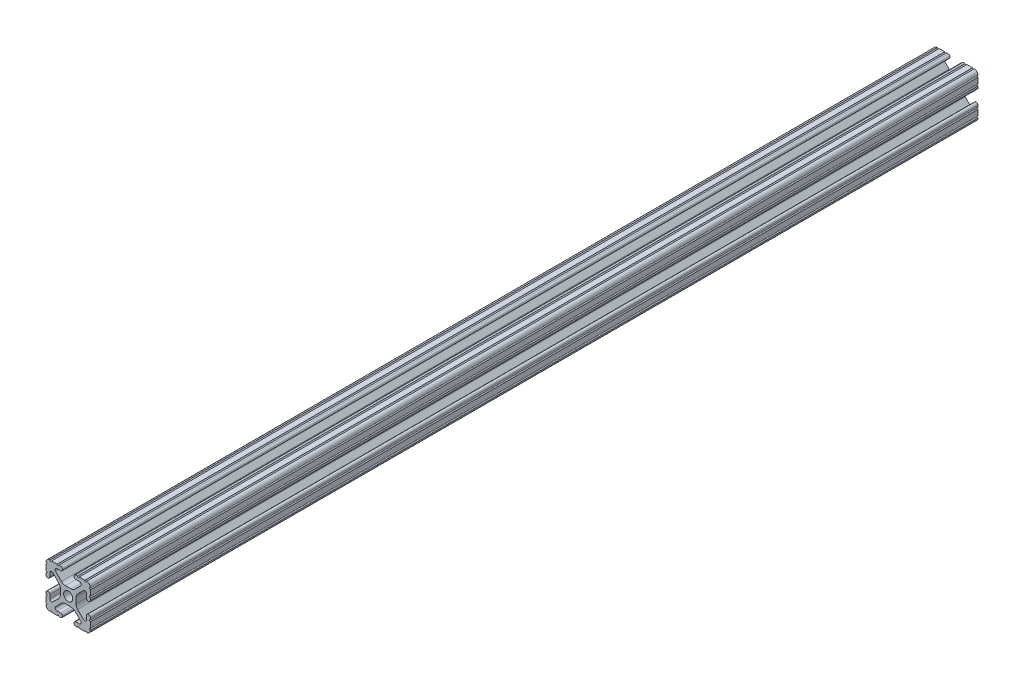
SolidWorks part; units mm, degrees
ref_plane "Front Plane" through (0, 0, 0) normal (0, 0, 1) x (1, 0, 0)
ref_plane "Top Plane" through (0, 0, 0) normal (0, 1, 0) x (1, 0, 0)
ref_plane "Right Plane" through (0, 0, 0) normal (1, 0, 0) x (0, 0, -1)
ref_plane "Plane1" through (0, 0, -25.4) normal (0, 0, -1) x (-1, 0, 0)
sketch "Sketch1" plane through (0, 0, -25.4) normal (0, 0, -1) x (-1, 0, 0)
  line L0 (12.7, -9.5504) -> (12.7, -6.3331)
  line L1 (12.7, -5.3171) -> (12.7, -4.3434)
  line L2 (10.4902, -4.3434) -> (10.4902, -6.4748)
  line L3 (8.7558, -7.1932) -> (5.4257, -3.8632)
  line L4 (4.4958, -1.6181) -> (4.4958, 1.6181)
  line L5 (5.4257, 3.8632) -> (8.7558, 7.1932)
  line L6 (10.4902, 6.4748) -> (10.4902, 4.3434)
  line L7 (12.7, 4.3434) -> (12.7, 5.3171)
  line L8 (12.7, 6.3331) -> (12.7, 9.5504)
  line L9 (9.5504, 12.7) -> (6.3331, 12.7)
  line L10 (5.3171, 12.7) -> (4.3434, 12.7)
  line L11 (4.3434, 10.4902) -> (6.4748, 10.4902)
  line L12 (7.1932, 8.7558) -> (3.8632, 5.4257)
  line L13 (1.6181, 4.4958) -> (-1.6181, 4.4958)
  line L14 (-3.8632, 5.4257) -> (-7.1932, 8.7558)
  line L15 (-6.4748, 10.4902) -> (-4.3434, 10.4902)
  line L16 (-4.3434, 12.7) -> (-5.3171, 12.7)
  line L17 (-6.3331, 12.7) -> (-9.5504, 12.7)
  line L18 (-12.7, 9.5504) -> (-12.7, 6.3331)
  line L19 (-12.7, 5.3171) -> (-12.7, 4.3434)
  line L20 (-10.4902, 4.3434) -> (-10.4902, 6.4748)
  line L21 (-8.7558, 7.1932) -> (-5.4257, 3.8632)
  line L22 (-4.4958, 1.6181) -> (-4.4958, -1.6181)
  line L23 (-5.4257, -3.8632) -> (-8.7558, -7.1932)
  line L24 (-10.4902, -6.4748) -> (-10.4902, -4.3434)
  line L25 (-12.7, -4.3434) -> (-12.7, -5.3171)
  line L26 (-12.7, -6.3331) -> (-12.7, -9.5504)
  line L27 (-9.5504, -12.7) -> (-6.3331, -12.7)
  line L28 (-5.3171, -12.7) -> (-4.3434, -12.7)
  line L29 (-4.3434, -10.4902) -> (-6.4748, -10.4902)
  line L30 (-7.1932, -8.7558) -> (-3.8632, -5.4257)
  line L31 (-1.6181, -4.4958) -> (1.6181, -4.4958)
  line L32 (3.8632, -5.4257) -> (7.1932, -8.7558)
  line L33 (6.4748, -10.4902) -> (4.3434, -10.4902)
  line L34 (4.3434, -12.7) -> (5.3171, -12.7)
  line L35 (6.3331, -12.7) -> (9.5504, -12.7)
  arc A0 (12.6998, -10.5664) -> (12.7, -9.5504) centre (12.7, -10.0584) cw
  arc A1 (12.7, -6.3331) -> (12.7, -5.3171) centre (12.7, -5.8251) cw
  arc A2 (12.7, -4.3434) -> (10.4902, -4.3434) centre (11.5951, -4.3434) ccw
  arc A3 (10.4902, -6.4748) -> (8.7558, -7.1932) centre (9.4742, -6.4748) cw
  arc A4 (5.4257, -3.8632) -> (4.4958, -1.6181) centre (7.6708, -1.6181) cw
  arc A5 (4.4958, 1.6181) -> (5.4257, 3.8632) centre (7.6708, 1.6181) cw
  arc A6 (8.7558, 7.1932) -> (10.4902, 6.4748) centre (9.4742, 6.4748) cw
  arc A7 (10.4902, 4.3434) -> (12.7, 4.3434) centre (11.5951, 4.3434) ccw
  arc A8 (12.7, 5.3171) -> (12.7, 6.3331) centre (12.7, 5.8251) cw
  arc A9 (12.7, 9.5504) -> (12.6998, 10.5664) centre (12.7, 10.0584) cw
  arc A10 (12.6998, 10.5664) -> (10.5664, 12.6998) centre (10.5918, 10.5918) ccw
  arc A11 (10.5664, 12.6998) -> (9.5504, 12.7) centre (10.0584, 12.7) cw
  arc A12 (6.3331, 12.7) -> (5.3171, 12.7) centre (5.8251, 12.7) cw
  arc A13 (4.3434, 12.7) -> (4.3434, 10.4902) centre (4.3434, 11.5951) ccw
  arc A14 (6.4748, 10.4902) -> (7.1932, 8.7558) centre (6.4748, 9.4742) cw
  arc A15 (3.8632, 5.4257) -> (1.6181, 4.4958) centre (1.6181, 7.6708) cw
  arc A16 (-1.6181, 4.4958) -> (-3.8632, 5.4257) centre (-1.6181, 7.6708) cw
  arc A17 (-7.1932, 8.7558) -> (-6.4748, 10.4902) centre (-6.4748, 9.4742) cw
  arc A18 (-4.3434, 10.4902) -> (-4.3434, 12.7) centre (-4.3434, 11.5951) ccw
  arc A19 (-5.3171, 12.7) -> (-6.3331, 12.7) centre (-5.8251, 12.7) cw
  arc A20 (-9.5504, 12.7) -> (-10.5664, 12.6998) centre (-10.0584, 12.7) cw
  arc A21 (-10.5664, 12.6998) -> (-12.6998, 10.5664) centre (-10.5918, 10.5918) ccw
  arc A22 (-12.6998, 10.5664) -> (-12.7, 9.5504) centre (-12.7, 10.0584) cw
  arc A23 (-12.7, 6.3331) -> (-12.7, 5.3171) centre (-12.7, 5.8251) cw
  arc A24 (-12.7, 4.3434) -> (-10.4902, 4.3434) centre (-11.5951, 4.3434) ccw
  arc A25 (-10.4902, 6.4748) -> (-8.7558, 7.1932) centre (-9.4742, 6.4748) cw
  arc A26 (-5.4257, 3.8632) -> (-4.4958, 1.6181) centre (-7.6708, 1.6181) cw
  arc A27 (-4.4958, -1.6181) -> (-5.4257, -3.8632) centre (-7.6708, -1.6181) cw
  arc A28 (-8.7558, -7.1932) -> (-10.4902, -6.4748) centre (-9.4742, -6.4748) cw
  arc A29 (-10.4902, -4.3434) -> (-12.7, -4.3434) centre (-11.5951, -4.3434) ccw
  arc A30 (-12.7, -5.3171) -> (-12.7, -6.3331) centre (-12.7, -5.8251) cw
  arc A31 (-12.7, -9.5504) -> (-12.6998, -10.5664) centre (-12.7, -10.0584) cw
  arc A32 (-12.6998, -10.5664) -> (-10.5664, -12.6998) centre (-10.5918, -10.5918) ccw
  arc A33 (-10.5664, -12.6998) -> (-9.5504, -12.7) centre (-10.0584, -12.7) cw
  arc A34 (-6.3331, -12.7) -> (-5.3171, -12.7) centre (-5.8251, -12.7) cw
  arc A35 (-4.3434, -12.7) -> (-4.3434, -10.4902) centre (-4.3434, -11.5951) ccw
  arc A36 (-6.4748, -10.4902) -> (-7.1932, -8.7558) centre (-6.4748, -9.4742) cw
  arc A37 (-3.8632, -5.4257) -> (-1.6181, -4.4958) centre (-1.6181, -7.6708) cw
  arc A38 (1.6181, -4.4958) -> (3.8632, -5.4257) centre (1.6181, -7.6708) cw
  arc A39 (7.1932, -8.7558) -> (6.4748, -10.4902) centre (6.4748, -9.4742) cw
  arc A40 (4.3434, -10.4902) -> (4.3434, -12.7) centre (4.3434, -11.5951) ccw
  arc A41 (5.3171, -12.7) -> (6.3331, -12.7) centre (5.8251, -12.7) cw
  arc A42 (9.5504, -12.7) -> (10.5664, -12.6998) centre (10.0584, -12.7) cw
  arc A43 (10.5664, -12.6998) -> (12.6998, -10.5664) centre (10.5918, -10.5918) ccw
  circle A44 centre (0, 0) radius 2.6035
extrude "Boss-Extrude1" add sketch "Sketch1" against normal blind 508
